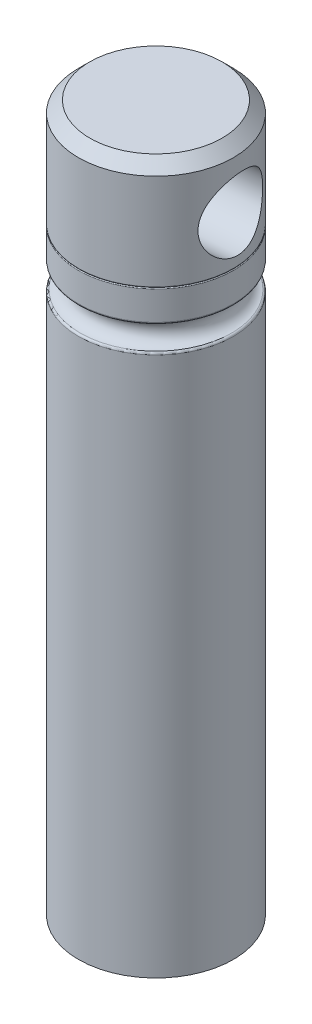
SolidWorks part; units mm, degrees
ref_plane "Front Plane" through (0, 0, 0) normal (0, 0, 1) x (1, 0, 0)
ref_plane "Top Plane" through (0, 0, 0) normal (0, 1, 0) x (1, 0, 0)
ref_plane "Right Plane" through (0, 0, 0) normal (1, 0, 0) x (0, 0, -1)
ref_plane "Plane1" through (0, 0, 75.1372) normal (0, 0, -1) x (-1, 0, 0)
sketch "Sketch1" plane through (0, 0, 75.1372) normal (0, 0, -1) x (-1, 0, 0)
  line L0 (30.3449, 74.5839) -> (44.6324, 74.5839)
  line L1 (44.6324, 74.5839) -> (44.6324, 204.7589)
  line L2 (44.6324, 204.7589) -> (30.3449, 204.7589)
  line L3 (30.3449, 204.7589) -> (30.3449, 184.9977)
  line L4 (30.3449, 184.6421) -> (30.3449, 178.9779)
  line L5 (30.3449, 174.4694) -> (30.3449, 74.5839)
  line L6 (44.6324, 74.5839) -> (44.6324, 204.7589) construction
  line L7 (30.3449, 174.4694) -> (44.6324, 174.4694) construction
  arc A0 (30.3449, 184.9977) -> (30.5227, 184.8199) centre (30.5227, 184.9977) ccw
  arc A1 (30.5227, 184.8199) -> (30.3449, 184.6421) centre (30.5227, 184.6421) ccw
  arc A2 (30.3449, 178.9779) -> (30.3449, 174.4694) centre (30.3449, 176.7237) cw
  dimension "D1" = 130.175
  dimension "D2" = 99.8855
revolve "Revolve1" add sketch "Sketch1" angle 360 about L6
hole_wizard "M12 Clearance Hole1" positions "3DSketch1" profile "Sketch2" hole size "M12" standard "ANSI Metric"
sketch3d "3DSketch1"
  point P0 (-30.3927, 193.1638, 73.9698)
sketch "Sketch2" plane through (-30.3927, 193.1638, 73.9698) normal (0, 1, 0) x (-0.0817, 0, -0.9967)
  line L0 (0, 0) -> (0, 29.6947)
  line L1 (0, 29.6947) -> (6.5151, 29.6947)
  line L2 (6.5151, 29.6947) -> (6.5151, 0)
  line L5 (6.5151, 0) -> (0, 0)
  line L11 (0, -6.35) -> (0, 107.95) construction
  dimension "Thru Hole Dia." = 13.0302
  dimension "Thru Hole Depth" = 29.6947
chamfer "Chamfer2" distance 2.0828 angle 45 1 edges at (-44.6324, 204.7589, 89.4247)
fillet "Fillet1" radius 0.381 2 edges at (-44.6324, 178.9779, 89.4247) (-44.6324, 174.4694, 89.4247)
